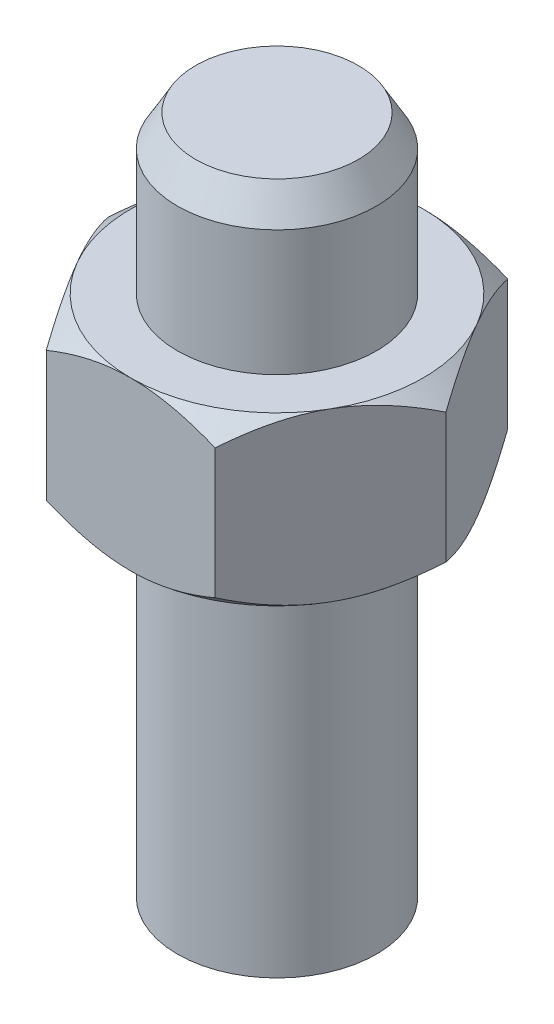
SolidWorks part; units mm, degrees
ref_plane "Alzado" through (0, 0, 0) normal (0, 0, 1) x (1, 0, 0)
ref_plane "Planta" through (0, 0, 0) normal (0, 1, 0) x (1, 0, 0)
ref_plane "Vista lateral" through (0, 0, 0) normal (1, 0, 0) x (0, 0, -1)
sketch "Croquis1" plane through (0, 0, 0) normal (0, 1, 0) x (1, 0, 0)
  circle A0 centre (0, 0) radius 9.525
  dimension "D1" = 19.05
extrude "Saliente-Extruir1" add sketch "Croquis1" along normal blind 50
sketch "Croquis3" plane through (0, 50, 0) normal (0, 1, 0) x (1, 0, 0)
  line L1 (16.1658, 0) -> (8.0829, 14)
  line L2 (8.0829, 14) -> (-8.0829, 14)
  line L3 (-8.0829, 14) -> (-16.1658, 0)
  line L4 (-16.1658, 0) -> (-8.0829, -14)
  line L5 (-8.0829, -14) -> (8.0829, -14)
  line L6 (8.0829, -14) -> (16.1658, 0)
  circle A0 centre (0, 0) radius 14 construction
  circle A1 centre (0, 0) radius 9.525
  dimension "D1" = 28
extrude "Saliente-Extruir2" add sketch "Croquis3" against normal blind 16
sketch "Croquis4" plane through (0, 50, 0) normal (0, 1, 0) x (1, 0, 0)
  circle A0 centre (0, 0) radius 9.525
  dimension "D1" = 19.05
extrude "Saliente-Extruir3" add sketch "Croquis4" along normal blind 15
chamfer "Chaflán1" distance 3 angle 30 1 edges at (0, 65, 9.525)
sketch "Croquis5" plane through (0, 50, 0) normal (0, 1, 0) x (1, 0, 0)
  circle A0 centre (0, 0) radius 14
  circle A1 centre (0, 0) radius 52.6938
extrude "Cortar-Extruir1" cut sketch "Croquis5" against normal blind 15 draft 51
sketch "Croquis6" plane through (0, 34, 0) normal (0, -1, 0) x (1, 0, 0)
  circle A0 centre (0, 0) radius 14
  circle A1 centre (0, 0) radius 45.1589
extrude "Cortar-Extruir2" cut sketch "Croquis6" against normal blind 15 draft 50
